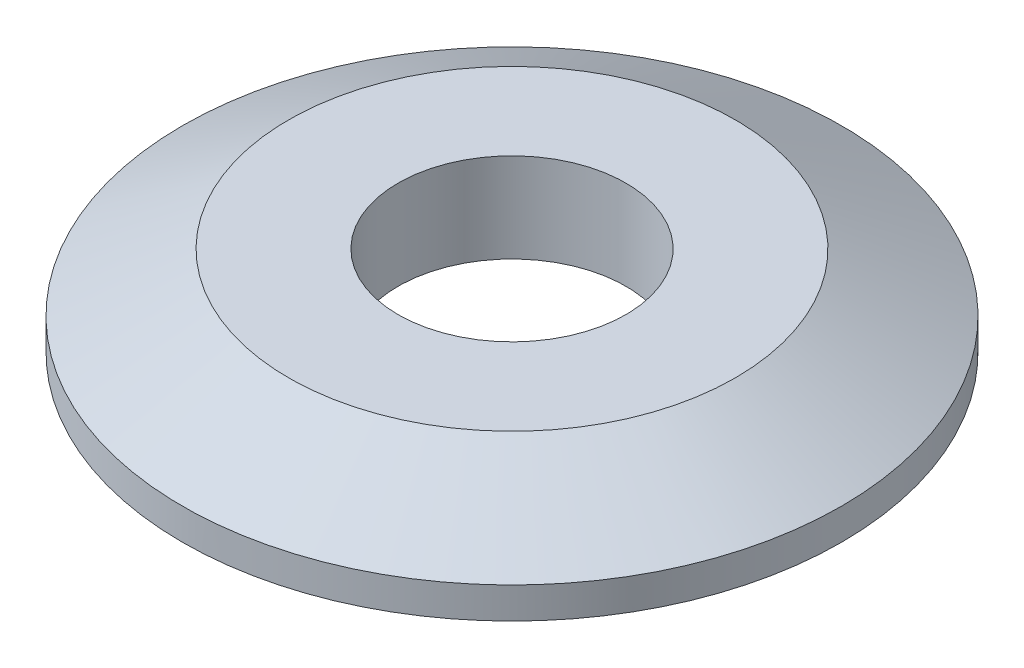
SolidWorks part; units mm, degrees
ref_plane "Front Plane" through (0, 0, 0) normal (0, 0, 1) x (1, 0, 0)
ref_plane "Top Plane" through (0, 0, 0) normal (0, 1, 0) x (1, 0, 0)
ref_plane "Right Plane" through (0, 0, 0) normal (1, 0, 0) x (0, 0, -1)
sketch "Sketch1" plane through (0, 0, 0) normal (0, 1, 0) x (1, 0, 0)
  circle A0 centre (0, 0) radius 7.375
  circle A1 centre (0, 0) radius 2.55
  dimension "D1" = 5.1
  dimension "D2" = 14.75
extrude "Boss-Extrude1" add sketch "Sketch1" along normal blind 2
sketch "Sketch2" plane through (0, 0, 0) normal (0, 0, 1) x (1, 0, 0)
  line L0 (0, 0) -> (0, 2) construction
  line L1 (7.375, 2) -> (-7.375, 2) construction
  line L2 (5, 2) -> (7.375, 0.7)
  line L3 (2.55, 2) -> (-2.55, 2) construction
  line L4 (7.375, 0) -> (7.375, 2) construction
  line L5 (7.375, 0.7) -> (7.375, 2)
  line L6 (7.375, 2) -> (5, 2)
  dimension "D1" = 10
  dimension "D2" = 0.7
revolve "Cut-Revolve1" cut sketch "Sketch2" angle 360 about L0
